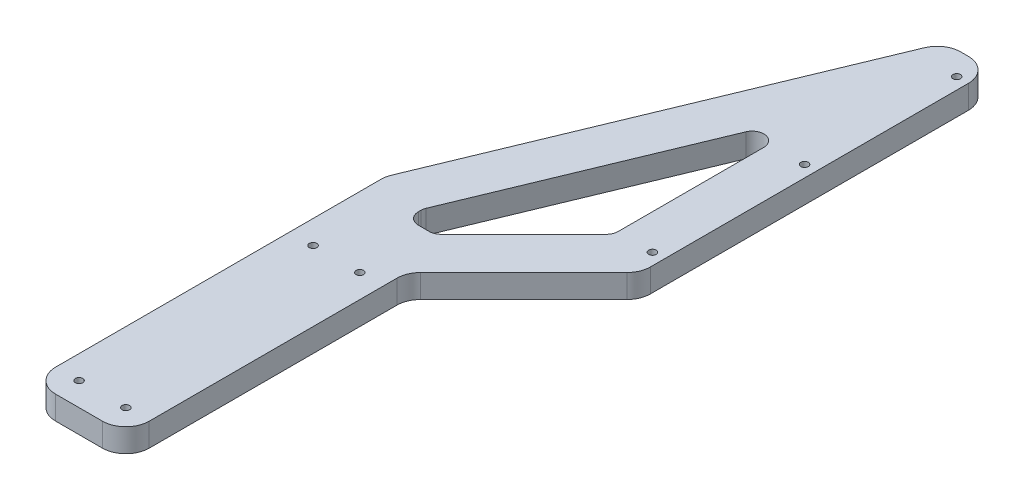
SolidWorks part; units mm, degrees
material "Acrylic (Medium-high impact)"
ref_plane "Front Plane" through (0, 0, 0) normal (0, 0, 1) x (1, 0, 0)
ref_plane "Top Plane" through (0, 0, 0) normal (0, 1, 0) x (1, 0, 0)
ref_plane "Right Plane" through (0, 0, 0) normal (1, 0, 0) x (0, 0, -1)
sketch "Sketch1" plane through (0, 0, 0) normal (0, 1, 0) x (1, 0, 0)
  line L0 (0, 120) -> (0, 151.0051)
  line L1 (0, 0) -> (40, 0)
  line L2 (0, 0) -> (0, 120)
  line L3 (0, 120) -> (40, 120) construction
  line L4 (40, 0) -> (40, 120)
  line L5 (0, 151.0051) -> (70, 320)
  line L6 (70, 320) -> (90, 320)
  line L7 (90, 320) -> (90, 170)
  line L8 (90, 170) -> (40, 120)
  line L9 (20, 147.0268) -> (70, 267.7375)
  line L10 (70, 267.7375) -> (70, 267.7375)
  line L11 (70, 267.7375) -> (70, 178.2843)
  line L12 (70, 178.2843) -> (31.7157, 140)
  line L13 (20, 140) -> (31.7157, 140)
  line L14 (20, 140) -> (20, 147.0268)
  dimension "D1" = 40
  dimension "D2" = 45
  dimension "D3" = 22.5
  dimension "D4" = 20
  dimension "D5" = 50
  dimension "D6" = 120
  dimension "D7" = 150
  dimension "D8" = 20
extrude "Boss-Extrude1" add sketch "Sketch1" along normal blind 10
sketch "Sketch2" plane through (0, 10, 0) normal (0, 1, 0) x (1, 0, 0)
  line L0 (0, 151.0051) -> (0, 0) construction
  line L1 (10, 10) -> (30, 10) construction
  line L2 (10, 10) -> (10, 110) construction
  line L3 (10, 110) -> (30, 110) construction
  line L4 (30, 10) -> (30, 110) construction
  line L5 (0, 0) -> (40, 0) construction
  circle A0 centre (10, 110) radius 1.6
  circle A1 centre (30, 110) radius 1.6
  circle A2 centre (10, 10) radius 1.6
  circle A3 centre (30, 10) radius 1.6
  dimension "D3" = 3.2
  dimension "D1" = 100
  dimension "D2" = 20
  dimension "D4" = 10
  dimension "D5" = 10
extrude "Cut-Extrude1" cut sketch "Sketch2" against normal through all both and the other way through all
fillet "Fillet2" radius 5 5 edges at (20, 5, -147.0268) (31.7157, 5, -140) (20, 5, -140) (70, 5, -267.7375) (70, 5, -178.2843)
sketch "Sketch4" plane through (0, 10, 0) normal (0, 1, 0) x (1, 0, 0)
  line L0 (85, 310) -> (85, 180) construction
  line L1 (90, 170) -> (90, 320) construction
  line L2 (90, 320) -> (70, 320) construction
  circle A0 centre (85, 310) radius 1.6
  circle A1 centre (85, 245) radius 1.6
  circle A2 centre (85, 180) radius 1.6
  dimension "D1" = 3.2
  dimension "D2" = 5
  dimension "D3" = 10
  dimension "D4" = 130
extrude "Cut-Extrude3" cut sketch "Sketch4" against normal through all both and the other way through all
fillet "Fillet3" radius 10 7 edges at (0, 5, -151.0051) (0, 5, 0) (40, 5, 0) (40, 5, -120) (90, 5, -170) (90, 5, -320) (70, 5, -320)
